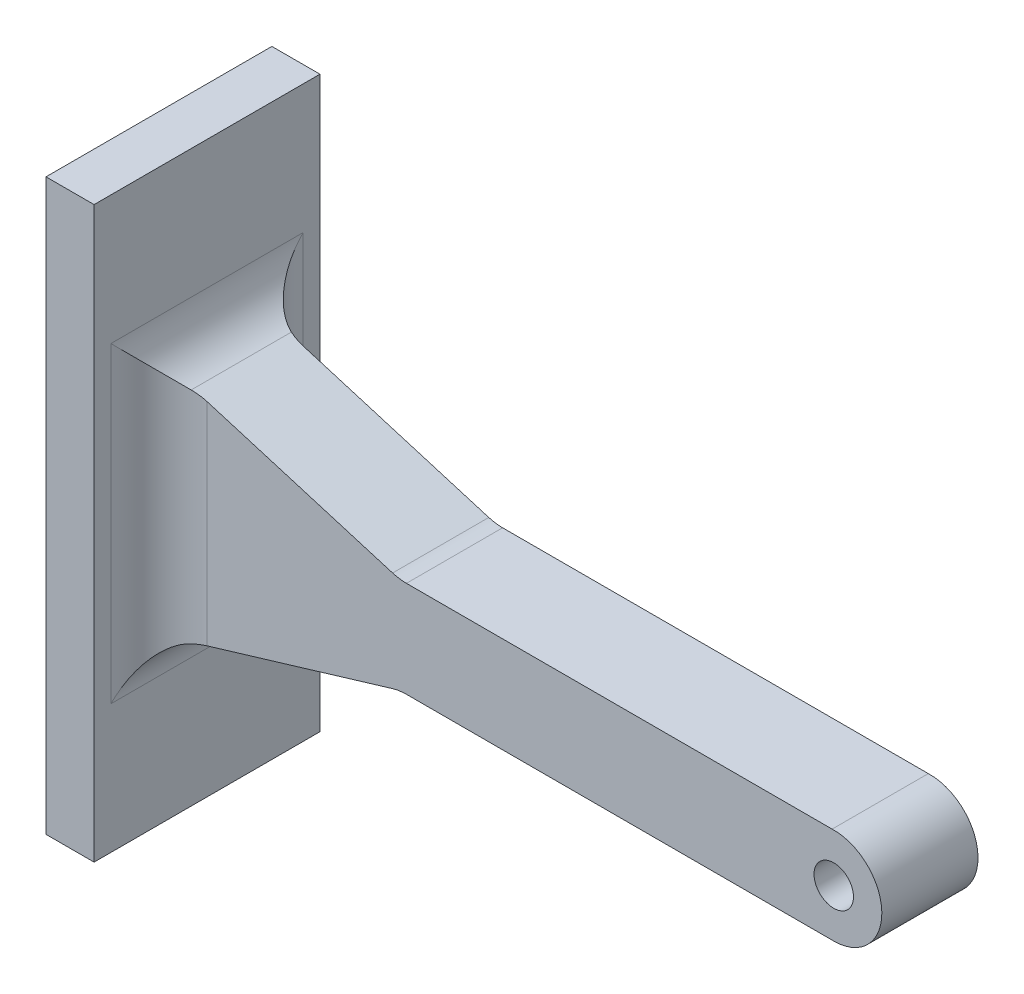
SolidWorks part; units mm, degrees
material "ABS"
ref_plane "前基準面" through (0, 0, 0) normal (0, 0, 1) x (1, 0, 0)
ref_plane "上基準面" through (0, 0, 0) normal (0, 1, 0) x (1, 0, 0)
ref_plane "右基準面" through (0, 0, 0) normal (1, 0, 0) x (0, 0, -1)
sketch "草圖1" plane through (0, 0, 0) normal (0, 0, 1) x (1, 0, 0)
  line L0 (-30.1678, 0) -> (15, 0) construction
  line L1 (-30.1678, 4.9972) -> (14.8322, 4.9972)
  line L2 (-30.1678, -4.9972) -> (15, -5)
  line L4 (-30.1678, 4.9972) -> (-55.1678, 12.5)
  line L5 (-55.1678, 12.5) -> (-55.1678, -12.5)
  line L6 (-55.1678, -12.5) -> (-30.1678, -4.9972)
  arc A1 (15, -5) -> (14.8322, 4.9972) centre (15, 0) ccw
  circle A3 centre (15, 0) radius 2.05
  point P3 (0, 0)
  dimension "D1" = 5
  dimension "D3" = 4.1
  dimension "D2" = 45
  dimension "D5" = 25
extrude "填料-伸長1" add sketch "草圖1" along normal mid plane 10
sketch "草圖3" plane through (-55.1678, 0, 0) normal (-1, 0, 0) x (0, 0, 1)
  line L1 (-11.7429, -29.6072) -> (11.7429, -29.6072)
  line L2 (-11.7429, -29.6072) -> (-11.7429, 29.6072)
  line L3 (-11.7429, 29.6072) -> (11.7429, 29.6072)
  line L4 (11.7429, -29.6072) -> (11.7429, 29.6072)
  line L5 (-11.7429, -29.6072) -> (11.7429, 29.6072) construction
  line L6 (-11.7429, 29.6072) -> (11.7429, -29.6072) construction
  point P0 (0, 0)
extrude "填料-伸長2" add sketch "草圖3" along normal blind 5
sketch "草圖4" plane through (0, 0, -5) normal (0, 0, -1) x (-1, 0, 0)
  line L1 (-16.6387, -2.6758) -> (-13.4162, -2.9382)
  line L2 (-13.4162, -2.9382) -> (-11.5777, -0.2787)
  line L3 (-11.5777, -0.2787) -> (-12.9617, 2.6433)
  line L4 (-12.9617, 2.6433) -> (-16.1842, 2.9057)
  line L5 (-16.1842, 2.9057) -> (-18.0227, 0.2461)
  line L6 (-18.0227, 0.2461) -> (-16.6387, -2.6758)
  circle A0 centre (-14.8002, -0.0163) radius 2.8 construction
  point P1 (-14.573, 2.7745)
  dimension "D1" = 5.6
extrude "除料-伸長1" cut sketch "草圖4" against normal blind 4
fillet "圓角1" radius 5 6 edges at (-55.1678, 0, 5) (-55.1678, 0, -5) (-55.1678, -12.5, 0) (-55.1678, 12.5, 0) (-30.1678, 4.9972, 0) (-30.1678, -4.9972, 0)
